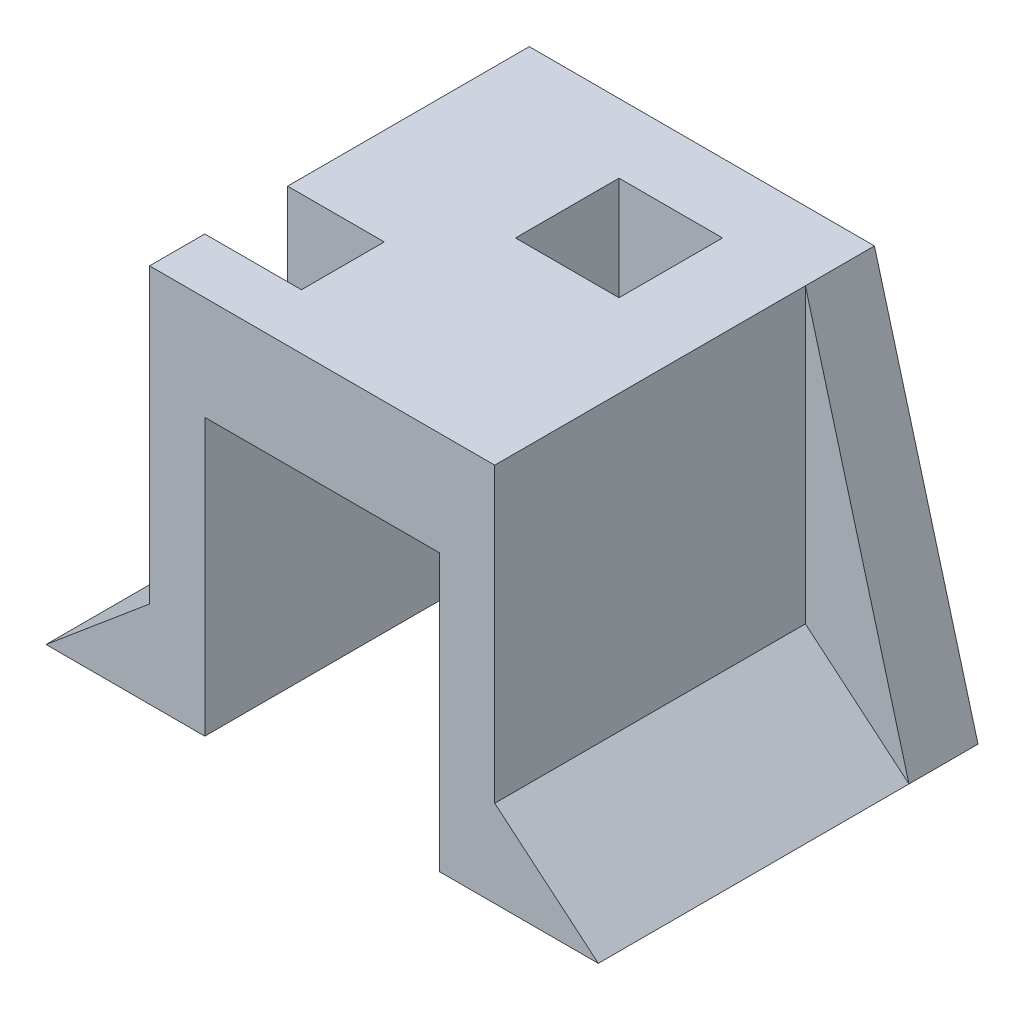
SolidWorks part; units mm, degrees
ref_plane "Спереди" through (0, 0, 0) normal (0, 0, 1) x (1, 0, 0)
ref_plane "Сверху" through (0, 0, 0) normal (0, 1, 0) x (1, 0, 0)
ref_plane "Справа" through (0, 0, 0) normal (1, 0, 0) x (0, 0, -1)
sketch "Эскиз1" plane through (0, 0, 0) normal (0, 0, 1) x (1, 0, 0)
  line L0 (-20, 12.5) -> (-3, 12.5)
  line L1 (-20, -27.5) -> (20, -27.5)
  line L2 (-20, -27.5) -> (-20, 27.5)
  line L3 (-20, 27.5) -> (20, 27.5)
  line L4 (20, -27.5) -> (20, 27.5)
  line L5 (-20, -27.5) -> (20, 27.5) construction
  line L6 (-20, 27.5) -> (20, -27.5) construction
  line L7 (-3, 12.5) -> (-3, -27.5)
  line L8 (5, 27.5) -> (5, -14.9135)
  line L9 (5, -14.9135) -> (20, -27.5)
  point P0 (0, 0)
  dimension "D1" = 55
  dimension "D2" = 40
  dimension "D3" = 25
  dimension "D4" = 17
  dimension "D5" = 40
  dimension "D6" = 40
extrude "Бобышка-Вытянуть1" add sketch "Эскиз1" along normal blind 55 contours L9 L8 L3 L2 L0 L7 L1
sketch "Эскиз2" plane through (0, 0, 0) normal (0, 0, -1) x (-1, 0, 0)
  line L0 (-5, 27.5) -> (-20, -27.5)
  line L1 (-20, -27.5) -> (-5, -14.9135)
  line L2 (-5, -14.9135) -> (-5, 27.5)
extrude "Бобышка-Вытянуть2" add sketch "Эскиз2" against normal blind 10
mirror "Зеркальное отражение1" about plane through (-20, 0, 55) normal (-1, 0, 0) of "Бобышка-Вытянуть2", "Бобышка-Вытянуть1"
sketch "Эскиз3" plane through (0, 27.5, 0) normal (0, 1, 0) x (1, 0, 0)
  line L0 (-45, 0) -> (5, 0) construction
  line L1 (-22, -25) -> (-7, -25)
  line L2 (-22, -25) -> (-22, -10)
  line L3 (-22, -10) -> (-7, -10)
  line L4 (-7, -25) -> (-7, -10)
  line L5 (-22, -25) -> (-7, -10) construction
  line L6 (-22, -10) -> (-7, -25) construction
  line L7 (5, -55) -> (5, -10) construction
  point P0 (-14.5, -17.5)
  dimension "D1" = 15
  dimension "D2" = 10
  dimension "D3" = 12
extrude "Вырез-Вытянуть1" cut sketch "Эскиз3" against normal through all
sketch "Эскиз4" plane through (0, 0, 55) normal (0, 0, 1) x (1, 0, 0)
  line L0 (-45, 27.5) -> (-45, 13.5)
  line L1 (-45, -14.9135) -> (-45, 27.5) construction
  line L2 (-45, 13.5) -> (-31, 27.5)
  line L3 (-45, 27.5) -> (5, 27.5) construction
  line L4 (-31, 27.5) -> (-45, 27.5)
  dimension "D1" = 14
extrude "Вырез-Вытянуть2" cut sketch "Эскиз4" against normal blind 12 from offset 8
